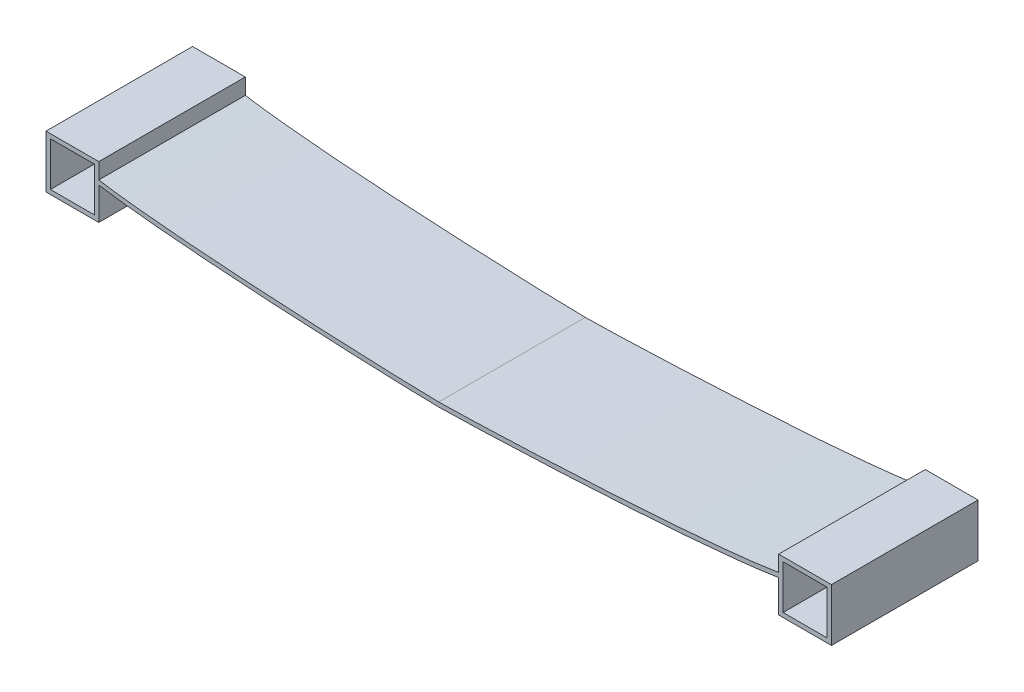
SolidWorks part; units mm, degrees
ref_plane "前视基准面" through (0, 0, 0) normal (0, 0, 1) x (1, 0, 0)
ref_plane "上视基准面" through (0, 0, 0) normal (0, 1, 0) x (1, 0, 0)
ref_plane "右视基准面" through (0, 0, 0) normal (1, 0, 0) x (0, 0, -1)
sketch "草图1" plane through (0, 0, 0) normal (0, 0, 1) x (1, 0, 0)
  line L0 (-147.1826, 113.815) -> (322.8174, 113.815) construction
  line L1 (-177.1826, 143.815) -> (-147.1826, 143.815)
  line L2 (-177.1826, 143.815) -> (-177.1826, 113.815)
  line L3 (-177.1826, 113.815) -> (-147.1826, 113.815)
  line L4 (-147.1826, 143.815) -> (-147.1826, 113.815)
  line L5 (322.8174, 143.815) -> (352.8174, 143.815)
  line L6 (322.8174, 143.815) -> (322.8174, 113.815)
  line L7 (322.8174, 113.815) -> (352.8174, 113.815)
  line L8 (352.8174, 143.815) -> (352.8174, 113.815)
  line L9 (322.8174, 113.815) -> (321.8764, 113.8247) construction
  line L10 (87.8174, 113.815) -> (87.8174, 272.5009) construction
  line L11 (-144.1826, 135.9333) -> (-84.0062, 126.1492) construction
  line L12 (-84.0062, 126.1492) -> (67.525, 120.7237) construction
  line L13 (67.525, 120.7237) -> (87.8174, 120.7237) construction
  line L14 (-144.1826, 132.9391) -> (-83.3547, 123.1513) construction
  line L15 (-83.3547, 123.1513) -> (67.1531, 117.7237) construction
  line L16 (67.1531, 117.7237) -> (87.8174, 117.7237) construction
  line L17 (319.8174, 132.9391) -> (258.9895, 123.1513) construction
  line L18 (258.9895, 123.1513) -> (108.4817, 117.7237) construction
  line L19 (108.4817, 117.7237) -> (87.8174, 117.7237) construction
  line L20 (319.8174, 135.9333) -> (259.641, 126.1492) construction
  line L21 (259.641, 126.1492) -> (108.1098, 120.7237) construction
  line L22 (108.1098, 120.7237) -> (87.8174, 120.7237) construction
  line L23 (-144.1826, 132.9391) -> (-144.1826, 110.815)
  line L24 (-180.1826, 146.815) -> (-144.1826, 146.815)
  line L25 (-180.1826, 146.815) -> (-180.1826, 110.815)
  line L26 (-180.1826, 110.815) -> (-144.1826, 110.815)
  line L27 (-144.1826, 146.815) -> (-144.1826, 135.9333)
  line L28 (319.8174, 146.815) -> (355.8174, 146.815)
  line L29 (319.8174, 146.815) -> (319.8174, 135.9333)
  line L30 (319.8174, 110.815) -> (355.8174, 110.815)
  line L31 (355.8174, 146.815) -> (355.8174, 110.815)
  line L32 (319.8174, 132.9391) -> (319.8174, 110.815)
  spline S0 degree 3 poles (-144.1826, 135.9333) (-84.0062, 126.1492) (67.525, 120.7237) (87.8174, 120.7237) knots 0 0 0 0 1 1 1 1
  spline S1 degree 3 poles (-144.1826, 132.9391) (-83.3547, 123.1513) (67.1531, 117.7237) (87.8174, 117.7237) knots 0 0 0 0 1 1 1 1
  spline S2 degree 3 poles (319.8174, 132.9391) (258.9895, 123.1513) (108.4817, 117.7237) (87.8174, 117.7237) knots 0 0 0 0 1 1 1 1
  spline S3 degree 3 poles (319.8174, 135.9333) (259.641, 126.1492) (108.1098, 120.7237) (87.8174, 120.7237) knots 0 0 0 0 1 1 1 1
  dimension "D1" = 30
  dimension "D2" = 30
  dimension "D3" = 30
  dimension "D4" = 30
  dimension "D5" = 470
  dimension "D7" = 3
  dimension "D10" = 3
  dimension "D11" = 3
  dimension "D12" = 3
  dimension "D13" = 3
  dimension "D14" = 3
  dimension "D15" = 3
  dimension "D16" = 3
  dimension "D17" = 3
extrude "凸台-拉伸1" add sketch "草图1" along normal blind 100
